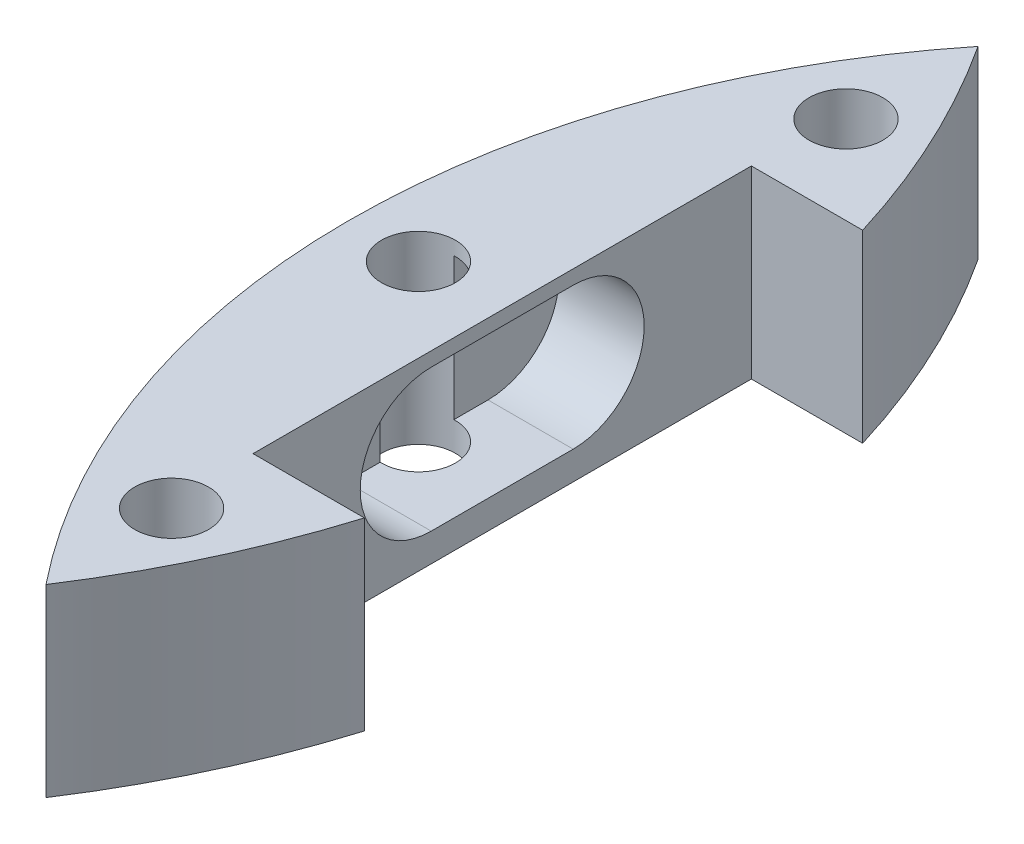
SolidWorks part; units mm, degrees
ref_plane "前视基准面" through (0, 0, 0) normal (0, 0, 1) x (1, 0, 0)
ref_plane "上视基准面" through (0, 0, 0) normal (0, 1, 0) x (1, 0, 0)
ref_plane "右视基准面" through (0, 0, 0) normal (1, 0, 0) x (0, 0, -1)
sketch "草图1" plane through (0, 0, 0) normal (0, 1, 0) x (1, 0, 0)
  line L0 (-41.1362, -23.75) -> (-41.1362, 23.75)
  line L1 (41, 17.55) -> (-41, 17.55)
  line L2 (41, 17.55) -> (41, -17.55)
  line L3 (41, -17.55) -> (-41, -17.55)
  line L4 (-41, 17.55) -> (-41, -17.55)
  line L5 (41, 17.55) -> (-41, -17.55) construction
  line L6 (41, -17.55) -> (-41, 17.55) construction
  line L7 (-41.1362, 23.75) -> (0, 0)
  line L8 (0, 0) -> (-41.1362, -23.75)
  line L9 (-41.1362, 0) -> (-91.1362, 0)
  circle A0 centre (0, 0) radius 52.45
  circle A1 centre (0, 0) radius 47.5
  circle A2 centre (-41.1362, -23.75) radius 2.6
  circle A3 centre (-41.1362, 23.75) radius 2.6
  circle A4 centre (-91.1362, 0) radius 60
  circle A5 centre (-47.5, 0) radius 2.6
  dimension "D1" = 104.9
  dimension "D4" = 95
  dimension "D7" = 5.2
  dimension "D8" = 5.2
  dimension "D11" = 120
  dimension "D12" = 5.2
  dimension "D2" = 35.1
  dimension "D3" = 41
  dimension "D5" = 60
  dimension "D6" = 90
  dimension "D9" = 50
  dimension "D10" = 0
extrude "凸台-拉伸1" add sketch "草图1" along normal blind 13 contours A5 L9 A0 A4 A1 A2 | A1 A4 L3 L8 A2 | A3 L0 A2 L8 L3 L4 L1 L7 | A5 A1 A2 L0 L9 | A5 L9 L0 A3 A1 | A5 A1 A3 A4 A0 L9 | L1 A4 A1 A3 L7
sketch "草图2" plane through (0, 13, 0) normal (0, 1, 0) x (1, 0, 0)
  line L0 (-33.7603, -17.55) -> (-41, -17.55) construction
  line L1 (-41, 17.55) -> (-41.6, 17.55)
  line L2 (-41, 17.55) -> (-41, -17.55)
  line L3 (-41, -17.55) -> (-41.6, -17.55)
  line L4 (-41.6, 17.55) -> (-41.6, -17.55)
  dimension "D1" = 0.6
  dimension "D2" = 0
extrude "切除-拉伸1" cut sketch "草图2" against normal blind 23
sketch "草图3" plane through (-41.6, 0, 0) normal (1, 0, 0) x (0, 0, -1)
  line L0 (-5, 7) -> (5, 7) construction
  line L1 (-5, 12) -> (5, 12)
  line L2 (-5, 2) -> (5, 2)
  line L3 (17.55, 0) -> (-17.55, 0) construction
  arc A0 (-5, 12) -> (-5, 2) centre (-5, 7) ccw
  arc A1 (5, 2) -> (5, 12) centre (5, 7) ccw
  point P2 (0, 7)
  dimension "D2" = 5
  dimension "D1" = 7
  dimension "D3" = 10
  dimension "D4" = 0
extrude "切除-拉伸2" cut sketch "草图3" against normal blind 6
